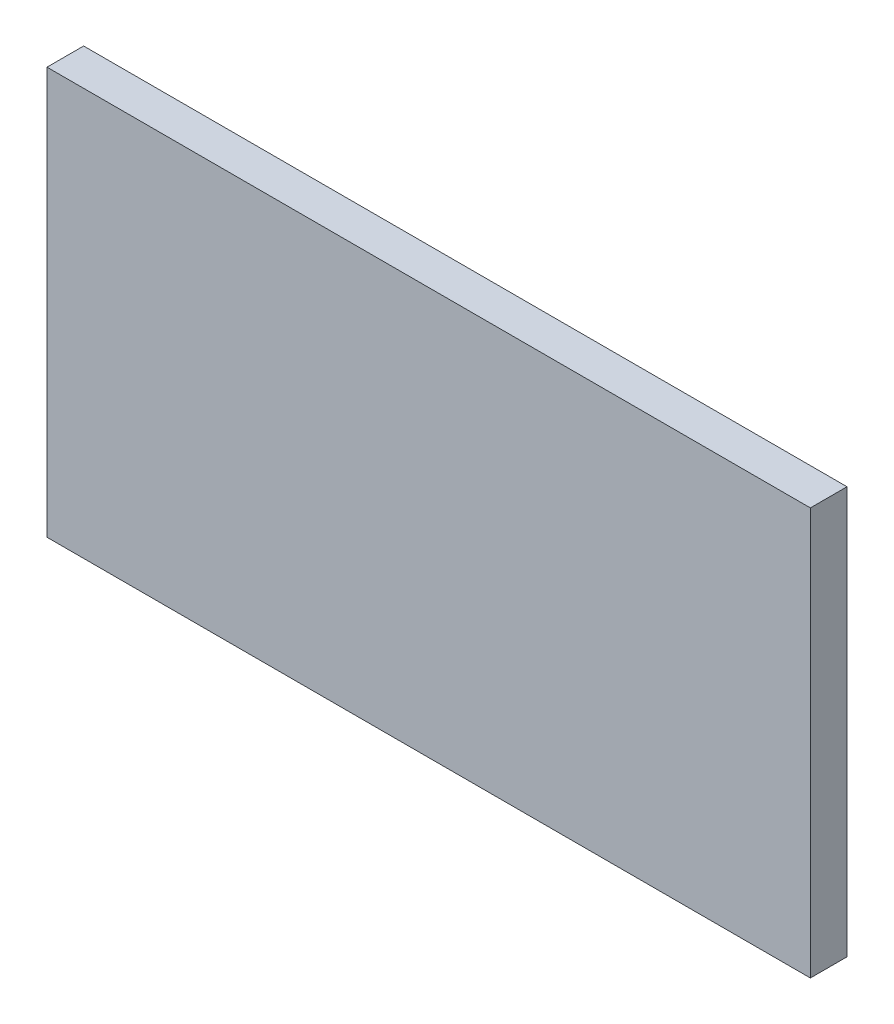
SolidWorks part; units mm, degrees
ref_plane "Alzado" through (0, 0, 0) normal (0, 0, 1) x (1, 0, 0)
ref_plane "Planta" through (0, 0, 0) normal (0, 1, 0) x (1, 0, 0)
ref_plane "Vista lateral" through (0, 0, 0) normal (1, 0, 0) x (0, 0, -1)
ref_plane "Plano_ParedChicaNorte" through (0, 50, 0) normal (0, 1, 0) x (1, 0, 0)
sketch "SkParedChicaNorte" plane through (0, 50, 0) normal (0, 1, 0) x (1, 0, 0)
  line L1 (-187.5, -205.5) -> (187.5, -205.5)
  line L2 (-187.5, -205.5) -> (-187.5, -187.5)
  line L3 (-187.5, -187.5) -> (187.5, -187.5)
  line L4 (187.5, -205.5) -> (187.5, -187.5)
extrude "ParedChicaNorte" add sketch "SkParedChicaNorte" along normal blind 200 separate body
